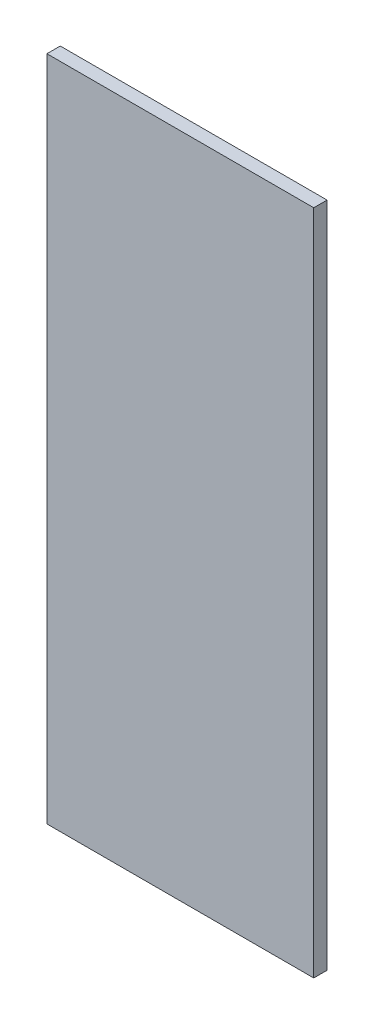
SolidWorks part; units mm, degrees
ref_plane "Front Plane" through (0, 0, 0) normal (0, 0, 1) x (1, 0, 0)
ref_plane "Top Plane" through (0, 0, 0) normal (0, 1, 0) x (1, 0, 0)
ref_plane "Right Plane" through (0, 0, 0) normal (1, 0, 0) x (0, 0, -1)
sketch "Sketch1" plane through (0, 0, 0) normal (0, 1, 0) x (1, 0, 0)
  line L1 (-20, 1) -> (20, 1)
  line L2 (-20, 1) -> (-20, -1)
  line L3 (-20, -1) -> (20, -1)
  line L4 (20, 1) -> (20, -1)
  dimension "D1" = 40
  dimension "D2" = 2
  dimension "D3" = 1
  dimension "D4" = 20
extrude "Boss-Extrude1" add sketch "Sketch1" along normal blind 100
